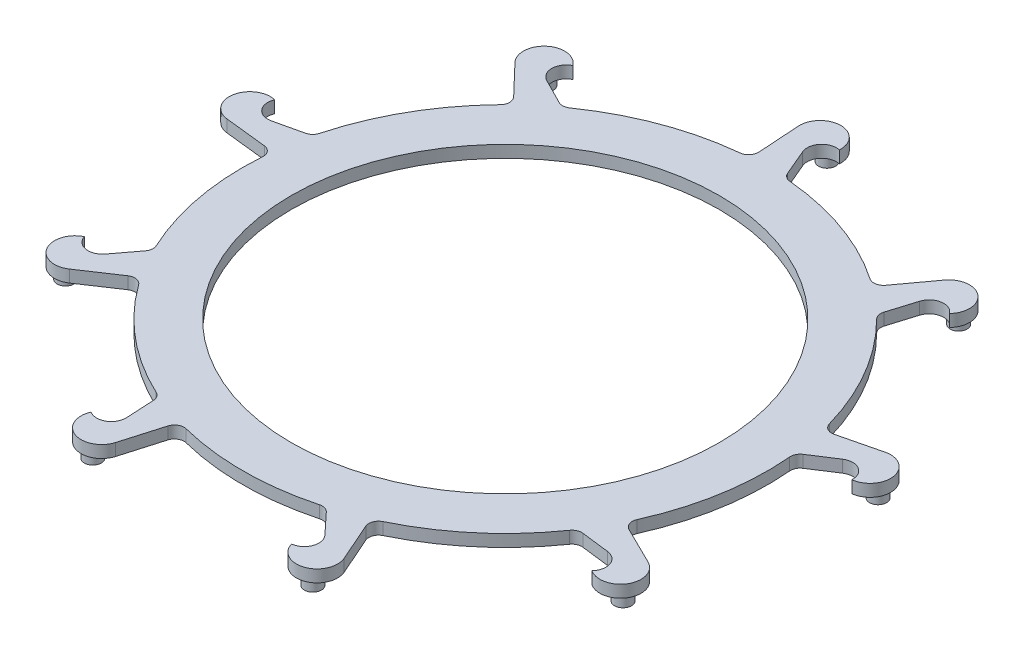
SolidWorks part; units mm, degrees
ref_plane "Front Plane" through (0, 0, 0) normal (0, 0, 1) x (1, 0, 0)
ref_plane "Top Plane" through (0, 0, 0) normal (0, 1, 0) x (1, 0, 0)
ref_plane "Right Plane" through (0, 0, 0) normal (1, 0, 0) x (0, 0, -1)
sketch "Sketch1" plane through (0, 0, 0) normal (0, 1, 0) x (1, 0, 0)
  circle A0 centre (0, 0) radius 55.9594
  circle A1 centre (0, 0) radius 68.6594
  dimension "D1" = 111.9188
  dimension "D2" = 12.7
extrude "Boss-Extrude1" add sketch "Sketch1" along normal blind 3.175
sketch "Sketch2" plane through (0, 3.175, 0) normal (0, 1, 0) x (1, 0, 0)
  line L0 (0, 0) -> (0, 135.9318) construction
  line L1 (0, 0) -> (-4.4905, 68.5124) construction
  line L2 (0, 0) -> (8.8904, 135.6408) construction
  line L3 (-4.6537, 71.0017) -> (-5.3728, 81.9729)
  line L4 (3.8894, 69.9338) -> (0.9836, 76.7774)
  line L5 (-4.6537, 71.0017) -> (-8.8904, 135.6408) construction
  arc A0 (-6.9318, 68.3086) -> (-4.6537, 71.0017) centre (-7.1883, 70.8356) ccw
  circle A1 centre (0, 0) radius 68.6594 construction
  arc A2 (5.3728, 81.9729) -> (-5.3728, 81.9729) centre (0, 82.3251) ccw
  arc A3 (5.3728, 81.9729) -> (0.9836, 76.7774) centre (4.4905, 78.2665) ccw
  arc A4 (6.0052, 68.3963) -> (-6.9318, 68.3086) centre (0, 0) ccw
  arc A5 (3.8894, 69.9338) -> (6.0052, 68.3963) centre (6.2274, 70.9265) ccw
  point P10 (4.4905, 68.5124)
  dimension "D2" = 7.62
  dimension "D3" = 19.05
  dimension "D4" = 5.3843
  dimension "D5" = 5.08
  dimension "D6" = 2.54
  dimension "D7" = 64.77
  dimension "D1" = 7.5
extrude "Boss-Extrude2" add sketch "Sketch2" against normal blind 3.175
pattern_circular "CirPattern1" count 9 over 360 about axis through (0, 0, 0) along (0, 1, 0) of "Boss-Extrude2"
sketch "Sketch3" plane through (0, 3.175, 0) normal (0, 1, 0) x (1, 0, 0)
  line L0 (0, 0) -> (0, 87.7094) construction
  circle A0 centre (0, 84.1322) radius 2.2225
  arc A4 (5.3728, 81.9729) -> (0.9836, 76.7774) centre (4.4905, 78.2665) ccw construction
  arc A5 (5.3728, 81.9729) -> (-5.3728, 81.9729) centre (0, 82.3251) ccw construction
  dimension "D1" = 4.445
  dimension "D2" = 1.3547
  dimension "D3" = 1.3547
sketch "Sketch4" plane through (0, 3.175, 0) normal (0, 1, 0) x (1, 0, 0)
  line L0 (0, 0) -> (0, 105.2172) construction
  line L1 (0, 0) -> (35.9864, 98.8719) construction
  line L2 (21.0579, 57.8562) -> (6.0052, 68.3963) construction
  line L3 (18.2672, 60.4622) -> (6.0052, 68.3963)
  line L4 (24.8709, 58.0587) -> (38.5978, 56.7831)
  arc A0 (38.5978, 56.7831) -> (6.0052, 68.3963) centre (0, 0) ccw construction
  arc A1 (38.5978, 56.7831) -> (6.0052, 68.3963) centre (0, 0) ccw
  arc A2 (5.3728, 81.9729) -> (-5.3728, 81.9729) centre (0, 82.3251) ccw construction
  arc A3 (5.3728, 81.9729) -> (-5.3728, 81.9729) centre (0, 82.3251) ccw construction
  arc A4 (18.2672, 60.4622) -> (24.8709, 58.0587) centre (22.9646, 63.0948) ccw
  dimension "D2" = 75
  dimension "D3" = 5.3848
  dimension "D1" = 20
  dimension "D4" = 14.605
extrude "Cut-Extrude7" [suppressed] cut sketch "Sketch4" against normal through all
pattern_circular "CirPattern12" [suppressed] count 9 over 360
fillet "Fillet1" [suppressed] radius 5.08
extrude "Boss-Extrude3" add sketch "Sketch3" against normal blind 6.35
pattern_circular "CirPattern13" count 9 over 360 about axis through (0, 0, 0) along (0, 1, 0) of "Boss-Extrude3"
